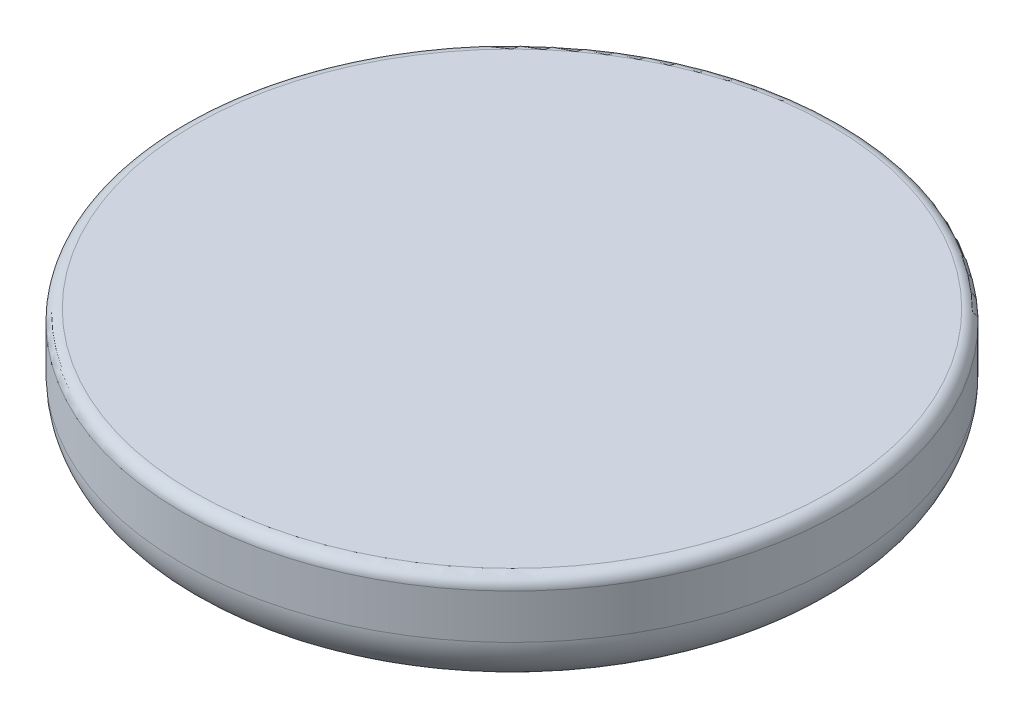
SolidWorks part; units mm, degrees
ref_plane "Front Plane" through (0, 0, 0) normal (0, 0, 1) x (1, 0, 0)
ref_plane "Top Plane" through (0, 0, 0) normal (0, 1, 0) x (1, 0, 0)
ref_plane "Right Plane" through (0, 0, 0) normal (1, 0, 0) x (0, 0, -1)
sketch "Sketch1" plane through (0, 0, 0) normal (0, 1, 0) x (1, 0, 0)
  circle A0 centre (0, 0) radius 10
  dimension "D1" = 20
extrude "Boss-Extrude1" add sketch "Sketch1" along normal blind 3.2
fillet "Fillet1" radius 0.35 1 edges at (0, 3.2, 10)
fillet "Fillet2" radius 1.5 1 edges at (0, 0, 10)
